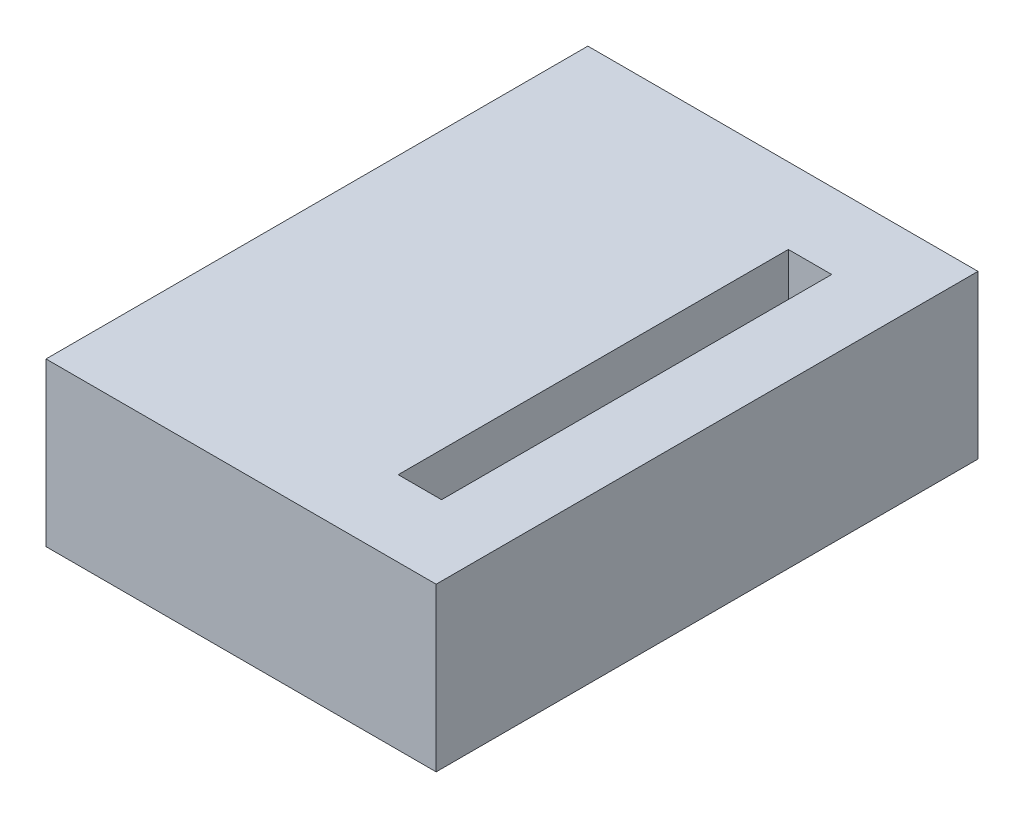
SolidWorks part; units mm, degrees
ref_plane "Front Plane" through (0, 0, 0) normal (0, 0, 1) x (1, 0, 0)
ref_plane "Top Plane" through (0, 0, 0) normal (0, 1, 0) x (1, 0, 0)
ref_plane "Right Plane" through (0, 0, 0) normal (1, 0, 0) x (0, 0, -1)
sketch "Sketch2" plane through (0, 0, 0) normal (0, 1, 0) x (1, 0, 0)
  line L1 (0, 0) -> (9.144, 0)
  line L2 (0, 0) -> (0, 12.7)
  line L3 (0, 12.7) -> (9.144, 12.7)
  line L4 (9.144, 0) -> (9.144, 12.7)
  dimension "D1" = 12.7
  dimension "D2" = 9.144
extrude "Boss-Extrude1" add sketch "Sketch2" along normal blind 3.81
sketch "Sketch4" plane through (0, 3.81, 0) normal (0, 1, 0) x (1, 0, 0)
  line L0 (9.144, 0) -> (9.144, 12.7) construction
  line L1 (7.493, 1.778) -> (6.477, 1.778)
  line L2 (7.493, 1.778) -> (7.493, 10.922)
  line L3 (7.493, 10.922) -> (6.477, 10.922)
  line L4 (6.477, 1.778) -> (6.477, 10.922)
  point P6 (7.493, 6.35)
  point P7 (9.144, 6.35)
  dimension "D1" = 2.667
  dimension "D2" = 1.016
  dimension "D3" = 9.144
  dimension "D4" = 0
extrude "Cut-Extrude1" cut sketch "Sketch4" against normal through all
